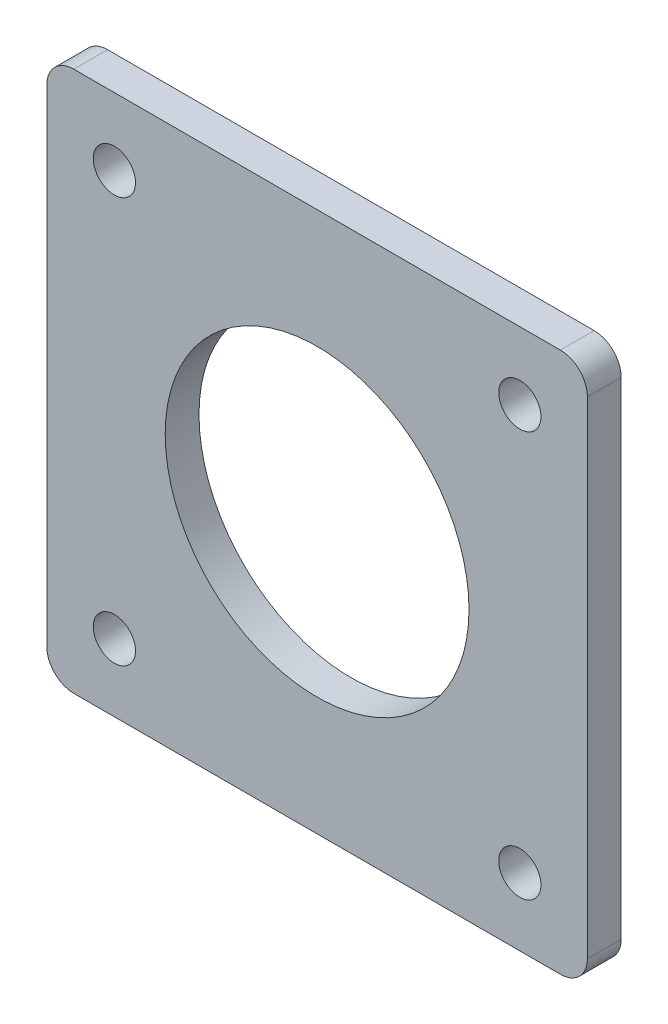
SolidWorks part; units mm, degrees
material "6061 Alloy"
ref_plane "Front Plane" through (0, 0, 0) normal (0, 0, 1) x (1, 0, 0)
ref_plane "Top Plane" through (0, 0, 0) normal (0, 1, 0) x (1, 0, 0)
ref_plane "Right Plane" through (0, 0, 0) normal (1, 0, 0) x (0, 0, -1)
sketch "Sketch1" plane through (0, 0, 0) normal (0, 0, 1) x (1, 0, 0)
  line L1 (25.4, -25.4) -> (-25.4, -25.4)
  line L2 (25.4, -25.4) -> (25.4, 25.4)
  line L3 (25.4, 25.4) -> (-25.4, 25.4)
  line L4 (-25.4, -25.4) -> (-25.4, 25.4)
  line L5 (25.4, -25.4) -> (-25.4, 25.4) construction
  line L6 (25.4, 25.4) -> (-25.4, -25.4) construction
  circle A0 centre (0, 0) radius 14.2748
  point P0 (0, 0)
  dimension "D2" = 28.5496
  dimension "D1" = 50.8
extrude "Boss-Extrude1" add sketch "Sketch1" along normal blind 3.175
fillet "Fillet1" radius 2.54 4 edges at (25.4, -25.4, 1.5875) (-25.4, -25.4, 1.5875) (25.4, 25.4, 1.5875) (-25.4, 25.4, 1.5875)
hole_wizard "5/32 (0.15625) Diameter Hole1" positions "Sketch2" profile "Sketch3" hole size "5/32" standard "ANSI Inch" end condition through all
sketch "Sketch2" plane through (0, 0, 3.175) normal (0, 0, 1) x (1, 0, 0)
  line L0 (22.86, 25.4) -> (-22.86, 25.4) construction
  line L1 (-25.4, 22.86) -> (-25.4, -22.86) construction
  line L2 (-22.86, -25.4) -> (22.86, -25.4) construction
  line L3 (25.4, -22.86) -> (25.4, 22.86) construction
  point P0 (-19.05, 19.05)
  point P2 (19.05, 19.05)
  point P4 (19.05, -19.05)
  point P6 (-19.05, -19.05)
  dimension "D1" = 6.35
  dimension "D2" = 6.35
  dimension "D3" = 6.35
  dimension "D4" = 6.35
  dimension "D5" = 6.35
  dimension "D6" = 6.35
  dimension "D7" = 6.35
  dimension "D8" = 6.35
sketch "Sketch3" plane through (-19.05, 19.05, 3.175) normal (1, 0, 0) x (0, -1, 0)
  line L0 (0, 0) -> (0, 3.175)
  line L1 (0, 3.175) -> (1.9844, 3.175)
  line L2 (1.9844, 3.175) -> (1.9844, 0)
  line L5 (1.9844, 0) -> (0, 0)
  line L11 (0, -6.35) -> (0, 107.95) construction
  dimension "Thru Hole Dia." = 3.9688
  dimension "Thru Hole Depth" = 3.175
